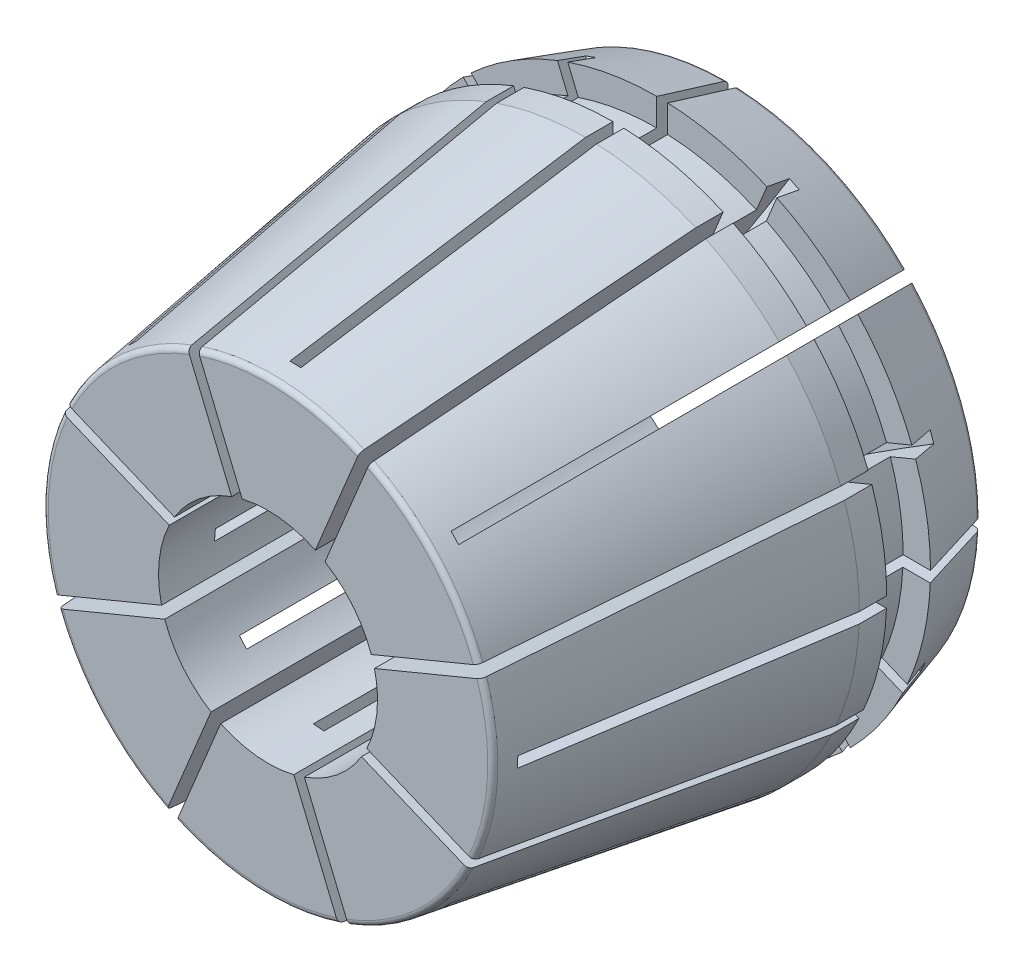
SolidWorks part; units mm, degrees
ref_plane "Front Plane" through (0, 0, 0) normal (0, 0, 1) x (1, 0, 0)
ref_plane "Top Plane" through (0, 0, 0) normal (0, 1, 0) x (1, 0, 0)
ref_plane "Right Plane" through (0, 0, 0) normal (1, 0, 0) x (0, 0, -1)
sketch "Sketch1" plane through (0, 0, 0) normal (0, 1, 0) x (1, 0, 0)
  line L0 (0, 58) -> (0, 100) construction
  line L1 (23, 100) -> (10, 100)
  line L2 (23, 100) -> (25, 93.5)
  line L3 (25, 93.5) -> (22.5, 93.5)
  line L4 (22.5, 93.5) -> (22.5, 89.5)
  line L5 (22.5, 89.5) -> (25, 89.5)
  line L6 (25, 89.5) -> (25, 87)
  line L7 (25, 87) -> (20.5, 58)
  line L8 (20.5, 58) -> (10, 58)
  line L9 (10, 100) -> (10, 58)
  dimension "D3" = 4
  dimension "D4" = 2.5
  dimension "D9" = 2.5
  dimension "D8" = 6.5
  dimension "D2" = 10
  dimension "D1" = 42
  dimension "D5" = 72.897
  dimension "D7" = 25
revolve "Revolve1" add sketch "Sketch1" angle 360 about L0
fillet "Fillet1" radius 0.5 1 edges at (23, 0, -100)
fillet "Fillet2" radius 0.5 1 edges at (20.5, 0, -58)
sketch "Sketch2" plane through (0, 0, 0) normal (1, 0, 0) x (0, 0, -1)
  line L1 (81, 0) -> (102, 0)
  line L5 (102, 0) -> (102, -21)
  arc A0 (81, 0) -> (102, -21) centre (81, -21) ccw
  dimension "D1" = 21
extrude "Cut-Extrude1" cut sketch "Sketch2" against normal blind 1
pattern_circular "CirPattern1" count 8 over 360 about axis through (0, 0, 0) along (0, 0, 1) of "Cut-Extrude1"
ref_plane "Plane1" through (0.2071, -0.5, 0) normal (-0.3827, 0.9239, 0) x (0.9239, 0.3827, 0)
sketch "Sketch4" plane through (0.2071, -0.5, 0) normal (-0.3827, 0.9239, 0) x (0.9239, 0.3827, 0)
  line L0 (22.6307, 100) -> (-22.6307, 100) construction
  line L1 (42.6742, 14.6516) -> (0, 14.6516)
  line L3 (0, 14.6516) -> (0, 57.3258)
  line L4 (0, 14.6516) -> (0, 57.3258)
  line L5 (22.6307, 100) -> (22.6307, 95)
  line L9 (0, 100) -> (22.6307, 100) construction
  arc A1 (42.6742, 14.6516) -> (0, 57.3258) centre (42.6742, 57.3258) ccw
  point P10 (22.6307, 100)
  dimension "D1" = 5
extrude "Cut-Extrude3" cut sketch "Sketch4" against normal blind 1
pattern_circular "CirPattern2" count 8 over 360 about axis through (0, 0, 0) along (0, 0, 1) of "Cut-Extrude3"
equation "\"colletheight\" = 42"
equation "\"slotdiam.offset\"= \"colletheight\" / 2"
equation "\"vial diam\"= 20"
equation "\"D2@Sketch1\"=\"vial diam\"/2"
equation "\"D1@Sketch1\"=\"colletheight\""
equation "\"D1@Sketch2\"=\"slotdiam.offset\""
